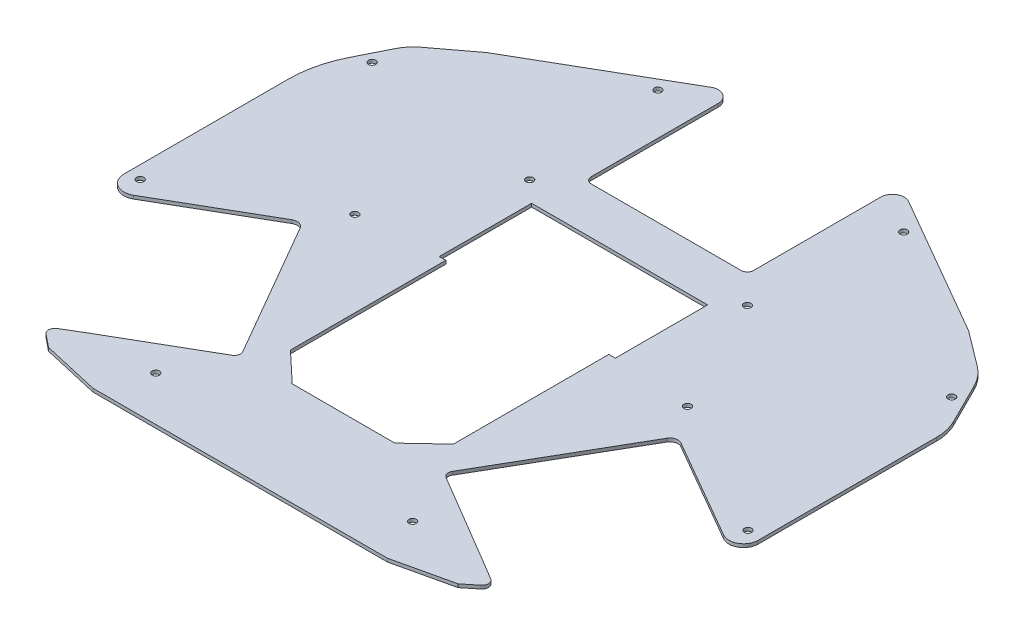
SolidWorks part; units mm, degrees
ref_plane "Front Plane" through (0, 0, 0) normal (0, 0, 1) x (1, 0, 0)
ref_plane "Top Plane" through (0, 0, 0) normal (0, 1, 0) x (1, 0, 0)
ref_plane "Right Plane" through (0, 0, 0) normal (1, 0, 0) x (0, 0, -1)
sketch "Sketch1" plane through (0, 0, 0) normal (0, 1, 0) x (1, 0, 0)
  line L0 (-31.5557, 63.2221) -> (-46.0224, 49.6064) construction
  line L5 (-46.0224, 49.6064) -> (-95.2644, 49.6064) construction
  line L6 (-95.2644, 49.6064) -> (-109.7311, 63.2221) construction
  line L7 (-109.7311, 63.2221) -> (-109.7311, 137.7742) construction
  line L8 (-112.8611, 137.7742) -> (-112.8611, 182.0493) construction
  line L9 (-112.8611, 182.0493) -> (-28.4257, 182.0493) construction
  line L10 (-28.4257, 182.0493) -> (-28.4257, 137.7742) construction
  line L11 (-31.5557, 137.7742) -> (-31.5557, 63.2221) construction
  line L12 (-31.5557, 63.2221) -> (-46.0224, 49.6064)
  line L13 (-46.0224, 49.6064) -> (-95.2644, 49.6064)
  line L14 (-95.2644, 49.6064) -> (-109.7311, 63.2221)
  line L15 (-109.7311, 63.2221) -> (-109.7311, 137.7742)
  line L16 (-112.8611, 137.7742) -> (-112.8611, 182.0493)
  line L17 (-112.8611, 182.0493) -> (-28.4257, 182.0493)
  line L18 (-28.4257, 182.0493) -> (-28.4257, 137.7742)
  line L19 (-31.5557, 137.7742) -> (-31.5557, 63.2221)
  line L20 (-109.7311, 137.7742) -> (-112.8611, 137.7742) construction
  line L21 (-109.7311, 137.7742) -> (-112.8611, 137.7742)
  line L22 (-28.4257, 137.7742) -> (-31.5557, 137.7742) construction
  line L23 (-28.4257, 137.7742) -> (-31.5557, 137.7742)
  line L24 (-70.6434, 0) -> (-70.6434, 204.3718) construction
  line L28 (24.6963, 21.4032) -> (-19.4149, 47.5637)
  line L29 (-20.4827, 51.644) -> (17.1624, 116.8472)
  line L30 (22.5258, 118.2844) -> (70.9878, 90.3048)
  line L31 (81.5046, 96.3767) -> (81.5046, 182.0252)
  line L32 (79.0144, 192.5903) -> (69.1441, 212.3646)
  line L33 (61.8119, 221.1775) -> (44.9931, 233.8542)
  line L34 (44.9931, 233.8542) -> (-23.1992, 273.2251)
  line L35 (-31.6912, 268.3222) -> (-31.6912, 207.3718)
  line L36 (-34.6912, 204.3718) -> (-106.5956, 204.3718)
  line L37 (-109.5956, 207.3718) -> (-109.5956, 268.3222)
  line L38 (-118.0876, 273.2251) -> (-186.28, 233.8542)
  line L39 (-186.28, 233.8542) -> (-204.215, 220.3362)
  line L40 (-209.8067, 213.6153) -> (-217.2476, 198.7079)
  line L41 (-222.7914, 175.1878) -> (-222.7914, 96.3767)
  line L42 (-211.6252, 89.9299) -> (-163.5124, 117.7078)
  line L43 (-158.0981, 116.257) -> (-120.4964, 51.1291)
  line L44 (-121.5945, 47.031) -> (-165.9831, 21.4032)
  line L45 (-165.9831, 21.4032) -> (-174.6764, 16.1829)
  line L46 (-175.0169, 11.2771) -> (-168.8601, 6.3045)
  line L47 (-168.8601, 6.3045) -> (-141.2868, 0)
  line L48 (-141.2868, 0) -> (0, 0)
  line L49 (0, 0) -> (27.5733, 6.3045)
  line L50 (27.5733, 6.3045) -> (33.7301, 11.2771)
  line L51 (33.3896, 16.1829) -> (24.6963, 21.4032)
  line L52 (24.6963, 21.4032) -> (-19.4149, 47.5637)
  line L53 (-20.4827, 51.644) -> (17.1624, 116.8472)
  line L54 (22.5258, 118.2844) -> (70.9878, 90.3048)
  line L55 (81.5046, 96.3767) -> (81.5046, 182.0252)
  line L56 (79.0144, 192.5903) -> (69.1441, 212.3646)
  line L57 (61.8119, 221.1775) -> (44.9931, 233.8542)
  line L58 (44.9931, 233.8542) -> (-23.1992, 273.2251)
  line L59 (-31.6912, 268.3222) -> (-31.6912, 207.3718)
  line L60 (-34.6912, 204.3718) -> (-106.5956, 204.3718)
  line L61 (-109.5956, 207.3718) -> (-109.5956, 268.3222)
  line L62 (-118.0876, 273.2251) -> (-186.28, 233.8542)
  line L63 (-186.28, 233.8542) -> (-204.215, 220.3362)
  line L64 (-209.8067, 213.6153) -> (-217.2476, 198.7079)
  line L65 (-222.7914, 175.1878) -> (-222.7914, 96.3767)
  line L66 (-211.6252, 89.9299) -> (-163.5124, 117.7078)
  line L67 (-158.0981, 116.257) -> (-120.4964, 51.1291)
  line L68 (-121.5945, 47.031) -> (-165.9831, 21.4032)
  line L69 (-165.9831, 21.4032) -> (-174.6764, 16.1829)
  line L70 (-175.0169, 11.2771) -> (-168.8601, 6.3045)
  line L71 (-168.8601, 6.3045) -> (-141.2868, 0)
  line L72 (-141.2868, 0) -> (0, 0)
  line L73 (0, 0) -> (27.5733, 6.3045)
  line L74 (27.5733, 6.3045) -> (33.7301, 11.2771)
  line L75 (33.3896, 16.1829) -> (24.6963, 21.4032)
  circle A0 centre (-123.0911, 191.3493) radius 1.75
  circle A1 centre (-216.6411, 98.0364) radius 1.75
  circle A2 centre (-18.6457, 191.3493) radius 1.75
  circle A3 centre (74.9143, 98.0364) radius 1.75
  circle A8 centre (-9.2457, 21.35) radius 1.75
  circle A9 centre (-132.4411, 21.35) radius 1.75
  circle A10 centre (-150.6414, 135.0493) radius 1.75
  circle A11 centre (8.9146, 135.0493) radius 1.75
  circle A12 centre (68.3543, 202.3493) radius 1.75
  circle A13 centre (-11.6912, 259.3718) radius 1.75
  circle A14 centre (-129.5956, 259.3718) radius 1.75
  circle A15 centre (-209.6411, 202.3493) radius 1.75
  arc A16 (-20.4827, 51.644) -> (-19.4149, 47.5637) centre (-17.8846, 50.144) ccw
  arc A17 (22.5258, 118.2844) -> (17.1624, 116.8472) centre (20.5627, 114.8841) ccw
  arc A18 (70.9878, 90.3048) -> (81.5046, 96.3767) centre (74.4934, 96.3767) ccw
  arc A19 (81.5046, 182.0252) -> (79.0144, 192.5903) centre (57.848, 182.0252) ccw
  arc A20 (69.1441, 212.3646) -> (61.8119, 221.1775) centre (46.7411, 201.1823) ccw
  arc A21 (-23.1992, 273.2251) -> (-31.6912, 268.3222) centre (-26.0299, 268.3222) ccw
  arc A22 (-34.6912, 204.3718) -> (-31.6912, 207.3718) centre (-34.6912, 207.3718) ccw
  arc A23 (-109.5956, 207.3718) -> (-106.5956, 204.3718) centre (-106.5956, 207.3718) ccw
  arc A24 (-109.5956, 268.3222) -> (-118.0876, 273.2251) centre (-115.257, 268.3222) ccw
  arc A25 (-204.215, 220.3362) -> (-209.8067, 213.6153) centre (-192.7216, 205.0873) ccw
  arc A26 (-217.2476, 198.7079) -> (-222.7914, 175.1878) centre (-170.1267, 175.1878) ccw
  arc A27 (-222.7914, 96.3767) -> (-211.6252, 89.9299) centre (-215.3473, 96.3767) ccw
  arc A28 (-158.0981, 116.257) -> (-163.5124, 117.7078) centre (-161.5306, 114.2753) ccw
  arc A29 (-121.5945, 47.031) -> (-120.4964, 51.1291) centre (-123.0945, 49.6291) ccw
  arc A30 (-174.6764, 16.1829) -> (-175.0169, 11.2771) centre (-173.132, 13.6109) ccw
  arc A31 (33.7301, 11.2771) -> (33.3896, 16.1829) centre (31.8452, 13.6109) ccw
  arc A32 (-20.4827, 51.644) -> (-19.4149, 47.5637) centre (-17.8846, 50.144) ccw
  arc A33 (22.5258, 118.2844) -> (17.1624, 116.8472) centre (20.5627, 114.8841) ccw
  arc A34 (70.9878, 90.3048) -> (81.5046, 96.3767) centre (74.4934, 96.3767) ccw
  arc A35 (81.5046, 182.0252) -> (79.0144, 192.5903) centre (57.848, 182.0252) ccw
  arc A36 (69.1441, 212.3646) -> (61.8119, 221.1775) centre (46.7411, 201.1823) ccw
  arc A37 (-23.1992, 273.2251) -> (-31.6912, 268.3222) centre (-26.0299, 268.3222) ccw
  arc A38 (-34.6912, 204.3718) -> (-31.6912, 207.3718) centre (-34.6912, 207.3718) ccw
  arc A39 (-109.5956, 207.3718) -> (-106.5956, 204.3718) centre (-106.5956, 207.3718) ccw
  arc A40 (-109.5956, 268.3222) -> (-118.0876, 273.2251) centre (-115.257, 268.3222) ccw
  arc A41 (-204.215, 220.3362) -> (-209.8067, 213.6153) centre (-192.7216, 205.0873) ccw
  arc A42 (-217.2476, 198.7079) -> (-222.7914, 175.1878) centre (-170.1267, 175.1878) ccw
  arc A43 (-222.7914, 96.3767) -> (-211.6252, 89.9299) centre (-215.3473, 96.3767) ccw
  arc A44 (-158.0981, 116.257) -> (-163.5124, 117.7078) centre (-161.5306, 114.2753) ccw
  arc A45 (-121.5945, 47.031) -> (-120.4964, 51.1291) centre (-123.0945, 49.6291) ccw
  arc A46 (-174.6764, 16.1829) -> (-175.0169, 11.2771) centre (-173.132, 13.6109) ccw
  arc A47 (33.7301, 11.2771) -> (33.3896, 16.1829) centre (31.8452, 13.6109) ccw
  dimension "D2" = 3.5
  dimension "D3" = 96.78
  dimension "D5" = 3.5
  dimension "D8" = 3.5
  dimension "D9" = 3.5
  dimension "D10" = 47
  dimension "D11" = 47
  dimension "D12" = 72.15
  dimension "D13" = 72.59
  dimension "D14" = 21.35
  dimension "D15" = 21.35
  dimension "D16" = 3.5
  dimension "D17" = 3.5
  dimension "D18" = 22.71
  dimension "D19" = 22.31
  dimension "D20" = 20
  dimension "D22" = 3.5
  dimension "D23" = 3.5
  dimension "D24" = 20
  dimension "D25" = 55
  dimension "D28" = 3.5
  dimension "D31" = 3.5
  dimension "D32" = 9.3
  dimension "D36" = 3.5
  dimension "D4" = 20.3
  dimension "D6" = 96.78
  dimension "D7" = 20.3
  dimension "D21" = 55
  dimension "D26" = 10.23
  dimension "D27" = 9.3
  dimension "D29" = 106.91
  dimension "D30" = 48.43
  dimension "D33" = 9.78
  dimension "D34" = 48.43
  dimension "D35" = 106.47
  dimension "D1" = 0
extrude "Boss-Extrude1" add sketch "Sketch1" along normal blind 1.6
sketch "Sketch2" plane through (0, 1.6, 0) normal (0, 1, 0) x (1, 0, 0)
  line L2 (81.5046, 96.3767) -> (81.5046, 182.0252) construction
  line L7 (-28.4257, 182.0493) -> (-112.8611, 182.0493) construction
  line L8 (49.9146, 158.0493) -> (74.9146, 158.0493)
  line L9 (74.9146, 158.0493) -> (74.9146, 183.0493)
  line L10 (74.9146, 183.0493) -> (49.9146, 183.0493)
  line L11 (49.9146, 183.0493) -> (49.9146, 158.0493)
  circle A1 centre (43.4146, 132.3664) radius 8.05
  circle A2 centre (40.1946, 186.7093) radius 1.75
  circle A3 centre (42.0046, 203.0493) radius 6
  dimension "D2" = 4.66
  dimension "D4" = 16.1
  dimension "D5" = 3.5
  dimension "D3" = 12
  dimension "D14" = 39.5
  dimension "D1" = 41.31
  dimension "D6" = 38.09
  dimension "D7" = 49.683
  dimension "D8" = 6.59
  dimension "D9" = 24
  dimension "D10" = 25
  dimension "D11" = 25
  dimension "D15" = 21
